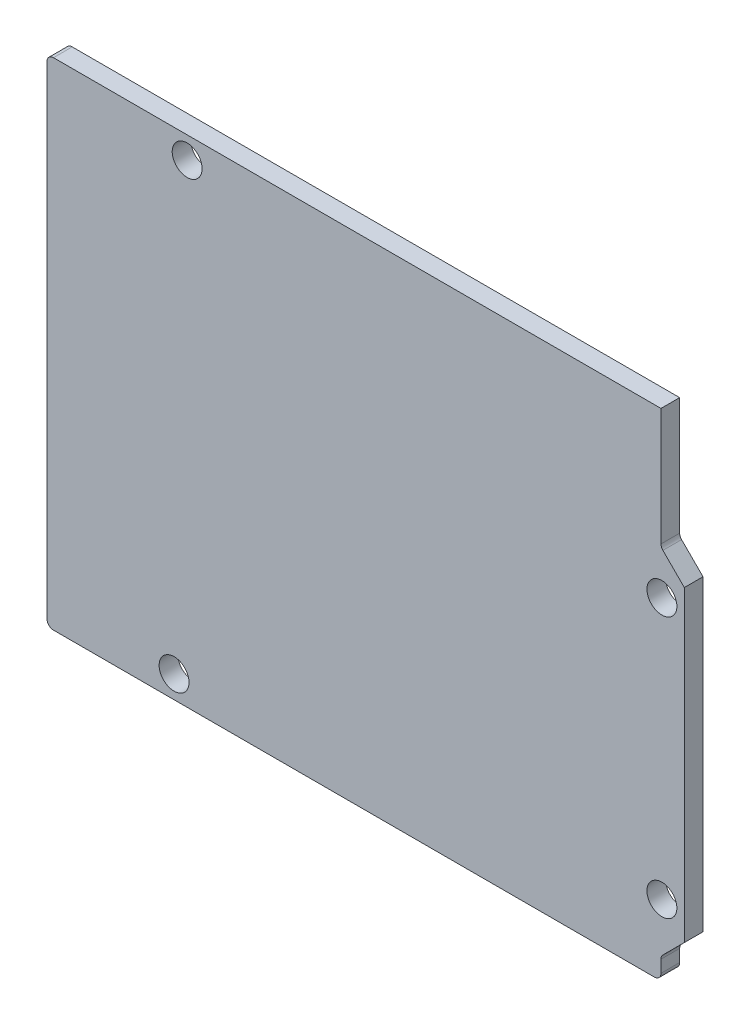
SolidWorks part; units mm, degrees
ref_plane "Front Plane" through (0, 0, 0) normal (0, 0, 1) x (1, 0, 0)
ref_plane "Top Plane" through (0, 0, 0) normal (0, 1, 0) x (1, 0, 0)
ref_plane "Right Plane" through (0, 0, 0) normal (1, 0, 0) x (0, 0, -1)
sketch "Sketch1" plane through (0, 0, 0) normal (0, 0, 1) x (1, 0, 0)
  line L8 (-35.808, -94.725) -> (28.492, -94.725)
  line L9 (29.192, -94.025) -> (29.192, -92.7149)
  line L10 (29.397, -92.22) -> (31.692, -89.925)
  line L11 (31.692, -89.925) -> (31.692, -57.025)
  line L12 (31.692, -57.025) -> (29.397, -54.73)
  line L13 (29.192, -54.2351) -> (29.192, -41.675)
  line L14 (29.192, -41.675) -> (-35.808, -41.675)
  line L15 (-36.508, -42.375) -> (-36.508, -94.025)
  line L16 (-35.808, -94.725) -> (28.492, -94.725)
  line L17 (29.192, -94.025) -> (29.192, -92.7149)
  line L18 (29.397, -92.22) -> (31.692, -89.925)
  line L19 (31.692, -89.925) -> (31.692, -57.025)
  line L20 (31.692, -57.025) -> (29.397, -54.73)
  line L21 (29.192, -54.2351) -> (29.192, -41.675)
  line L22 (29.192, -41.675) -> (-35.808, -41.675)
  line L23 (-36.508, -42.375) -> (-36.508, -94.025)
  circle A0 centre (29.292, -59.175) radius 1.6 construction
  circle A1 centre (29.292, -59.175) radius 1.6
  circle A2 centre (29.292, -87.125) radius 1.6 construction
  circle A3 centre (29.292, -87.125) radius 1.6
  circle A4 centre (-22.908, -92.325) radius 1.6 construction
  arc A5 (28.492, -94.725) -> (29.192, -94.025) centre (28.492, -94.025) ccw
  arc A6 (29.397, -92.22) -> (29.192, -92.7149) centre (29.892, -92.7149) ccw
  arc A7 (29.192, -54.2351) -> (29.397, -54.73) centre (29.892, -54.2351) ccw
  arc A8 (-35.808, -41.675) -> (-36.508, -42.375) centre (-35.808, -42.375) ccw
  arc A9 (-36.508, -94.025) -> (-35.808, -94.725) centre (-35.808, -94.025) ccw
  arc A10 (28.492, -94.725) -> (29.192, -94.025) centre (28.492, -94.025) ccw
  arc A11 (29.397, -92.22) -> (29.192, -92.7149) centre (29.892, -92.7149) ccw
  arc A12 (29.192, -54.2351) -> (29.397, -54.73) centre (29.892, -54.2351) ccw
  arc A13 (-35.808, -41.675) -> (-36.508, -42.375) centre (-35.808, -42.375) ccw
  arc A14 (-36.508, -94.025) -> (-35.808, -94.725) centre (-35.808, -94.025) ccw
  circle A15 centre (-22.908, -92.325) radius 1.6
  circle A16 centre (-22.908, -92.325) radius 1.6
  circle A17 centre (-21.508, -44.025) radius 1.6 construction
  circle A18 centre (-21.508, -44.025) radius 1.6
  dimension "D1" = 0
extrude "Boss-Extrude1" add sketch "Sketch1" along normal blind 2 from offset 2.5 contours L23 A14 L16 A10 L17 A11 L18 L19 L20 A12 L21 L22 A13 A18 A15 A1 A3
